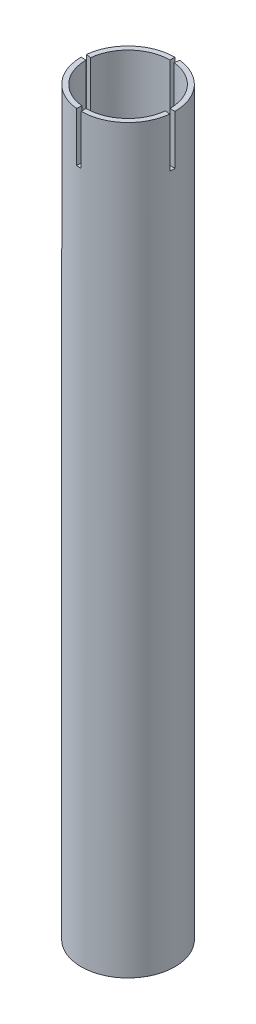
SolidWorks part; units mm, degrees
ref_plane "前视基准面" through (0, 0, 0) normal (0, 0, 1) x (1, 0, 0)
ref_plane "上视基准面" through (0, 0, 0) normal (0, 1, 0) x (1, 0, 0)
ref_plane "右视基准面" through (0, 0, 0) normal (1, 0, 0) x (0, 0, -1)
sketch "草图1" plane through (0, 0, 0) normal (0, 1, 0) x (1, 0, 0)
  circle A0 centre (0, 0) radius 17
  dimension "D1" = 34
extrude "拉伸-薄壁1" add sketch "草图1" along normal blind 300 thin
cosmetic thread "装饰螺纹线2" parameters "D1"=40, "D2"=36
sketch "草图3" plane through (0, 300, 0) normal (0, 1, 0) x (1, 0, 0)
  line L0 (0, 0) -> (0, 19)
  line L1 (0, 19) -> (2, 19)
  line L2 (2, 19) -> (0, 0)
  circle A0 centre (0, 0) radius 19 construction
  dimension "D1" = 2
extrude "切除-拉伸1" cut sketch "草图3" against normal blind 20
pattern_circular "阵列(圆周)1" count 4 over 360 about axis through (0, 300, 0) along (0, -1, 0) of "切除-拉伸1"
